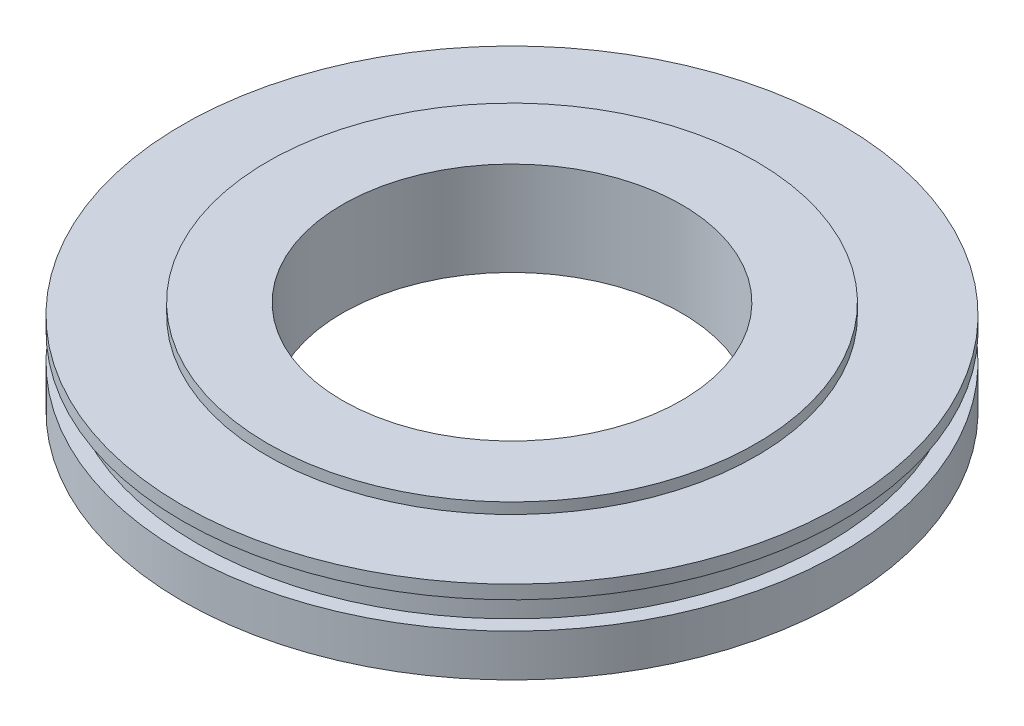
SolidWorks part; units mm, degrees
material "6061-T6 (SS)"
ref_plane "X-Y Datum" through (0, 0, 0) normal (0, 0, 1) x (1, 0, 0)
ref_plane "X-Z Datum" through (0, 0, 0) normal (0, 1, 0) x (1, 0, 0)
ref_plane "Y-Z Datum" through (0, 0, 0) normal (1, 0, 0) x (0, 0, -1)
sketch "Sketch1" plane through (0, 0, 0) normal (1, 0, 0) x (0, 0, -1)
  line L0 (-15.875, 2.6941) -> (-15.875, -5.0208)
  line L1 (-15.875, -5.0208) -> (-30.8407, -5.0208)
  line L3 (-30.8407, -1.0621) -> (-29.4348, -1.0621)
  line L4 (-29.4348, -1.0621) -> (-29.4348, 1.4779)
  line L5 (-29.4348, 1.4779) -> (-30.8407, 1.4779)
  line L6 (-30.8407, 1.4779) -> (-30.8407, 2.6941)
  line L7 (-30.8407, 2.6941) -> (-15.875, 2.6941)
  line L8 (0, 0) -> (0, -47872.0541) construction
  line L9 (0, 0) -> (-47872.0541, 0) construction
  line L10 (-30.8407, -1.0621) -> (-30.8407, -5.0208)
  line L11 (-14.7421, 2.6941) -> (15.0495, 2.6941) construction
  line L12 (-30.9994, 12.7) -> (-30.9994, -12.7) construction
  line L13 (14.2875, -5.0208) -> (-14.2875, -5.0208) construction
  line L14 (-29.3688, -1.0621) -> (29.3687, -1.0621) construction
  circle A0 centre (-30.3238, 0.2079) radius 0.889 construction
  point P15 (-30.9994, 0)
  point P16 (-29.4348, 0.2079)
  dimension "D3" = 1.778
  dimension "D1" = 31.75
  dimension "D2" = 61.6814
  dimension "D4" = 2.54
  dimension "D5" = 25.4
  dimension "D6" = 61.9989
  dimension "D7" = 1.5646
revolve "Revolve1" add sketch "Sketch1" angle 360 about L8
ref_plane "Plane1" through (0, 2.7479, 0) normal (0, -1, 0) x (-1, 0, 0)
sketch "Sketch3" plane through (0, 2.6941, 0) normal (0, 1, 0) x (1, 0, 0)
  circle A0 centre (0, 0) radius 30.8407
  circle A1 centre (0, 0) radius 15.875
  circle A2 centre (0, 0) radius 15.875 construction
  circle A3 centre (0, 0) radius 30.8407 construction
extrude "BandAid Solution thicker" add sketch "Sketch3" along normal up to surface (0.0538 mm away) up to plane "Plane1"
sketch "Sketch4" plane through (0, 2.7479, 0) normal (0, 1, 0) x (1, 0, 0)
  circle A0 centre (0, 0) radius 15.875
  circle A1 centre (0, 0) radius 22.86
  circle A2 centre (0, 0) radius 15.875 construction
  dimension "D1" = 45.72
extrude "Lip for Bearing" add sketch "Sketch4" along normal blind 1.016
